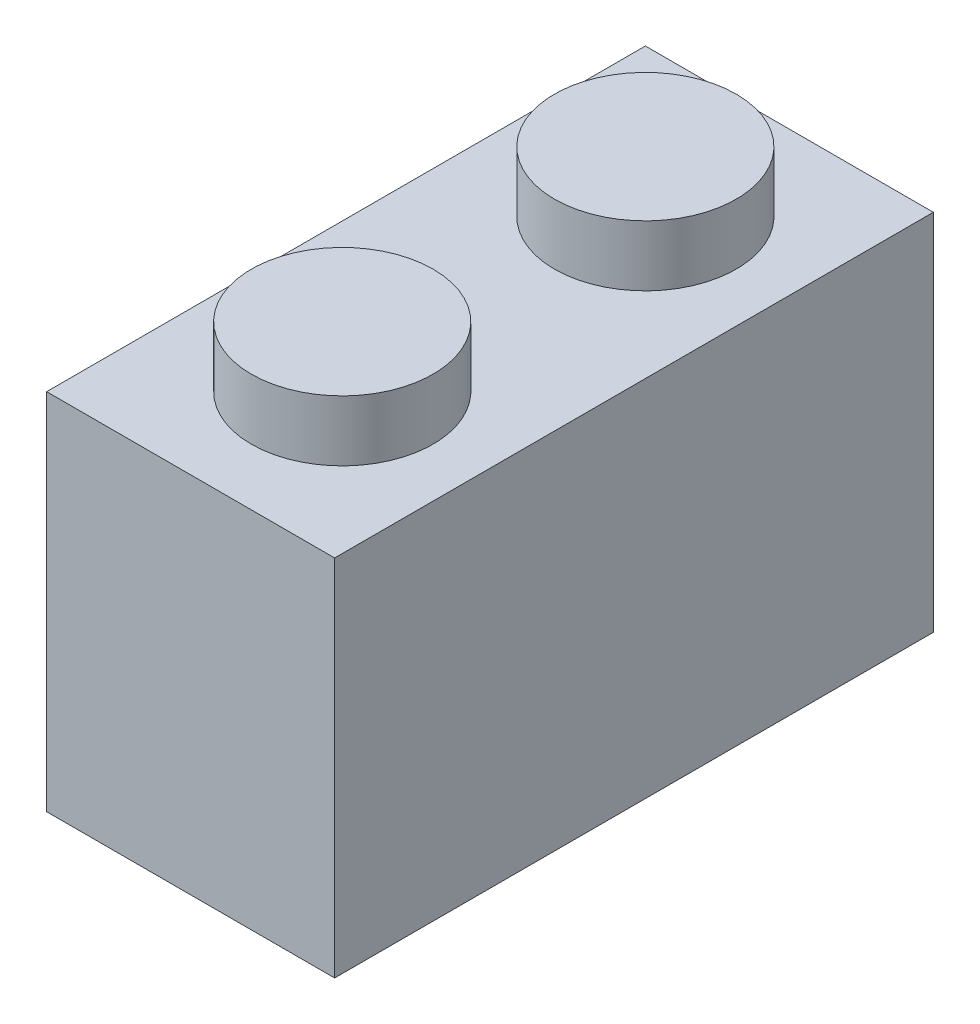
SolidWorks part; units mm, degrees
material "ABS"
ref_plane "Front Plane" through (0, 0, 0) normal (0, 0, 1) x (1, 0, 0)
ref_plane "Top Plane" through (0, 0, 0) normal (0, 1, 0) x (1, 0, 0)
ref_plane "Right Plane" through (0, 0, 0) normal (1, 0, 0) x (0, 0, -1)
sketch "Sketch1" plane through (0, 0, 0) normal (0, 0, 1) x (1, 0, 0)
  line L1 (0, 0) -> (7.6, 0)
  line L2 (0, 0) -> (0, 9.6)
  line L3 (0, 9.6) -> (7.6, 9.6)
  line L4 (7.6, 0) -> (7.6, 9.6)
  line L5 (0, 0) -> (7.6, 9.6) construction
  line L6 (0, 9.6) -> (7.6, 0) construction
  point P4 (3.8, 4.8)
  dimension "D1" = 7.6
  dimension "D2" = 9.6
extrude "Boss-Extrude1" add sketch "Sketch1" against normal blind 15.8
sketch "Sketch2" plane through (0, 9.6, 0) normal (0, 1, 0) x (1, 0, 0)
  line L0 (7.6, 0) -> (0, 0) construction
  circle A0 centre (3.9, 3.9) radius 2.4
  dimension "D1" = 4.8
  dimension "D2" = 3.9
  dimension "D3" = 3.9
extrude "Boss-Extrude2" add sketch "Sketch2" along normal blind 1.6
pattern_linear "LPattern1" count 2 spacing 8 along (0, 0, -1) count 4 spacing 8 along (-1, 0, 0) of "Boss-Extrude2"
shell "Shell1" thickness 1.2
sketch "Sketch4" plane through (0, 8.4, 0) normal (0, -1, 0) x (1, 0, 0)
  line L0 (0, -15.8) -> (0, 0) construction
  line L1 (0, 0) -> (7.6, 0) construction
  circle A0 centre (7.9, -7.9) radius 3.25
  circle A1 centre (7.9, -7.9) radius 2.4
  dimension "D1" = 4.8
  dimension "D2" = 6.5
  dimension "D3" = 7.9
  dimension "D4" = 7.9
extrude "Boss-Extrude3" [suppressed] add sketch "Sketch4" along normal offset from surface (8.2 mm away) 0.2
